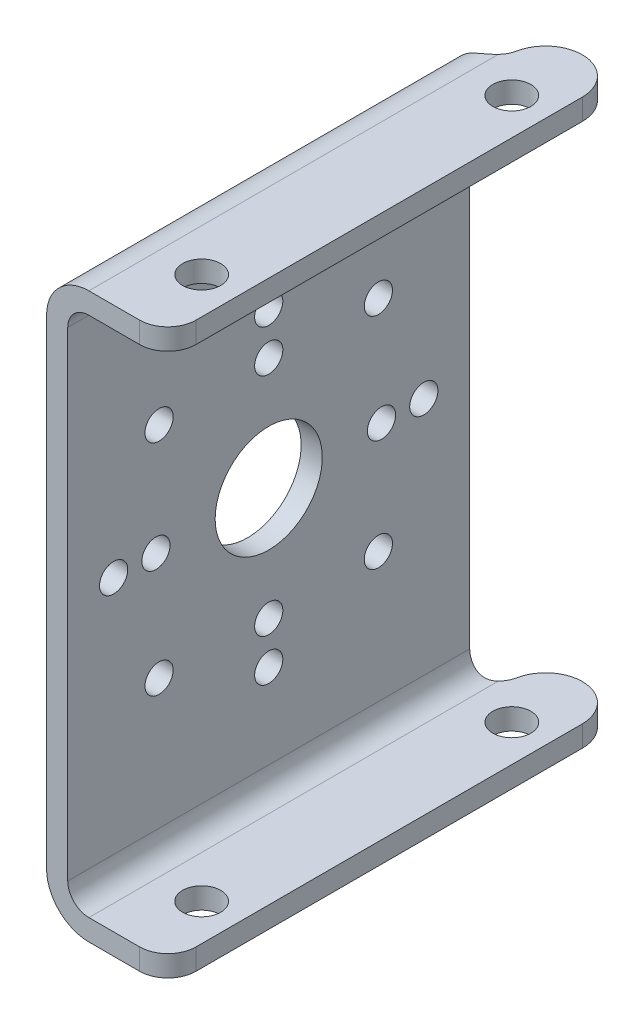
SolidWorks part; units mm, degrees
ref_plane "Ön Düzlem" through (0, 0, 0) normal (0, 0, 1) x (1, 0, 0)
ref_plane "Üst Düzlem" through (0, 0, 0) normal (0, 1, 0) x (1, 0, 0)
ref_plane "Sağ Düzlem" through (0, 0, 0) normal (1, 0, 0) x (0, 0, -1)
sketch "Sketch1" plane through (0, 0, 0) normal (0, 0, 1) x (1, 0, 0)
  line L0 (0, 0) -> (0, 40)
  line L1 (0, 40) -> (8.6, 40)
  line L2 (8.6, 40) -> (8.6, 38.5)
  line L3 (8.6, 38.5) -> (1.5, 38.5)
  line L4 (1.5, 38.5) -> (1.5, 1.5)
  line L5 (1.5, 1.5) -> (8.6, 1.5)
  line L6 (8.6, 1.5) -> (8.6, 0)
  line L7 (8.6, 0) -> (0, 0)
  dimension "D1" = 37
  dimension "D2" = 8.6
  dimension "D3" = 1.5
  dimension "D4" = 1.5
extrude "Boss-Extrude1" add sketch "Sketch1" along normal mid plane 32
sketch "Sketch2" plane through (0, 40, 0) normal (0, 1, 0) x (1, 0, 0)
  line L0 (6, 11) -> (6, -11) construction
  line L1 (0, 0) -> (6, 0) construction
  line L2 (8.6, -16) -> (8.6, 16) construction
  circle A0 centre (6, 11) radius 1.35
  circle A1 centre (6, -11) radius 1.35
  dimension "D2" = 2.7
  dimension "D1" = 22
  dimension "D3" = 2.6
extrude "Cut-Extrude1" cut sketch "Sketch2" against normal through all
sketch "Sketch4" plane through (0, 40, 0) normal (0, 1, 0) x (1, 0, 0)
  line L0 (8.6, 16) -> (0, 16) construction
  line L1 (8.6, -16) -> (8.6, 16) construction
  line L2 (6, 11) -> (6, 13.4) construction
  line L3 (0, -16) -> (0, 16) construction
  line L4 (1.7427, 12.5145) -> (0, 12.5145)
  line L5 (8.6, 13.4) -> (10.4287, 13.4)
  line L6 (10.4287, 13.4) -> (10.4287, 18.5661)
  line L7 (10.4287, 18.5661) -> (0, 18.5661)
  line L8 (0, 18.5661) -> (0, 12.5145)
  circle A0 centre (6, 13.4) radius 2.6
  circle A1 centre (1.7427, 14.2573) radius 1.7427
  line M3 (8.6, 16) -> (0, 16)
  line M4 (0, 16) -> (0, -16)
  line M6 (8.6, -16) -> (8.6, 16)
extrude "Cut-Extrude3" cut sketch "Sketch4" against normal through all contours A0 M6 M3 | L7 L8 L5 L6 M3 M6 | A1 A0 M3 | A1 | A1 M3 M4 | A1 L8 L4
sketch "Sketch3" plane through (0, 0, 0) normal (-1, 0, 0) x (0, 0, 1)
  line L0 (-12.5145, 20) -> (16, 20) construction
  line L2 (-12.5145, 0) -> (-12.5145, 40) construction
  line L3 (16, 40) -> (16, 0) construction
  circle A0 centre (1.7427, 20) radius 3.8
  dimension "D1" = 7.6
extrude "Cut-Extrude2" cut sketch "Sketch3" against normal through all
fillet "Fillet1" radius 3 2 edges at (0, 0, 1.7427) (0, 40, 1.7427)
fillet "Fillet2" radius 2 2 edges at (8.6, 0.75, 16) (8.6, 39.25, 16)
fillet "Fillet3" radius 1.5 2 edges at (1.5, 1.5, 1.7427) (1.5, 38.5, 1.7427)
sketch "Sketch5" plane through (1.5, 0, 0) normal (1, 0, 0) x (0, 0, -1)
  circle A0 centre (-1.7427, 20) radius 11 construction
  circle A1 centre (-1.7427, 31) radius 1
  dimension "D1" = 22
  dimension "D2" = 2
extrude "Cut-Extrude4" cut sketch "Sketch5" against normal up to next
pattern_circular "CirPattern1" count 8 over 360 about axis through (0, 20, 1.7427) along (1, 0, 0) of "Cut-Extrude4"
sketch "Sketch6" plane through (1.5, 0, 0) normal (1, 0, 0) x (0, 0, -1)
  circle A0 centre (-1.7427, 20) radius 8 construction
  circle A1 centre (-1.7427, 28) radius 1
  dimension "D1" = 16
  dimension "D2" = 2
extrude "Cut-Extrude5" cut sketch "Sketch6" against normal through all
pattern_circular "CirPattern2" count 4 over 360 about axis through (0, 20, 1.7427) along (1, 0, 0) of "Cut-Extrude5"
